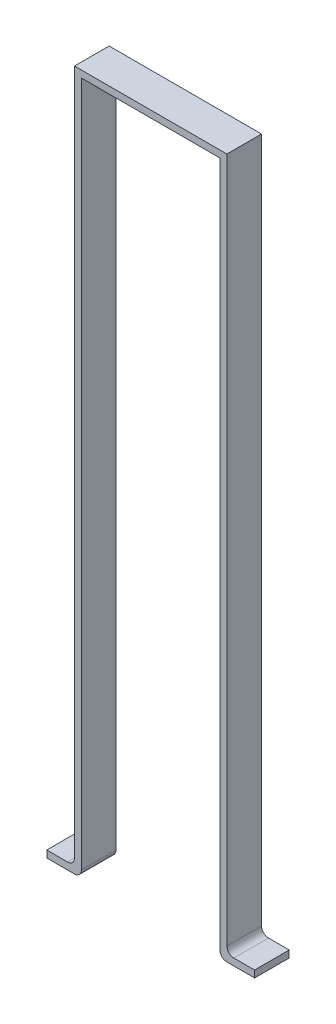
SolidWorks part; units mm, degrees
ref_plane "Front Plane" through (0, 0, 0) normal (0, 0, 1) x (1, 0, 0)
ref_plane "Top Plane" through (0, 0, 0) normal (0, 1, 0) x (1, 0, 0)
ref_plane "Right Plane" through (0, 0, 0) normal (1, 0, 0) x (0, 0, -1)
sketch "Sketch1" plane through (0, 0, 0) normal (0, 0, 1) x (1, 0, 0)
  line L0 (-25.4, 0) -> (25.4, 0) construction
  line L1 (-25.4, 2.54) -> (-25.4, 254)
  line L2 (-25.4, 254) -> (25.4, 254)
  line L3 (25.4, 254) -> (25.4, 2.54)
  line L4 (-27.94, 0) -> (-38.1, 0)
  line L5 (27.94, 0) -> (38.1, 0)
  line L6 (30.48, 2.54) -> (38.1, 2.54)
  line L7 (27.94, 256.54) -> (27.94, 5.08)
  line L8 (-27.94, 256.54) -> (27.94, 256.54)
  line L9 (-27.94, 5.08) -> (-27.94, 256.54)
  line L10 (-30.48, 2.54) -> (-38.1, 2.54)
  line L11 (-38.1, 2.54) -> (-38.1, 0)
  line L12 (38.1, 2.54) -> (38.1, 0)
  line L13 (-27.94, 2.54) -> (-27.94, 256.54) construction
  line L14 (-27.94, 2.54) -> (-38.1, 2.54) construction
  line L15 (-25.4, 0) -> (-38.1, 0) construction
  line L16 (-25.4, 0) -> (-25.4, 254) construction
  line L17 (25.4, 0) -> (38.1, 0) construction
  line L18 (25.4, 254) -> (25.4, 0) construction
  line L19 (27.94, 2.54) -> (38.1, 2.54) construction
  line L20 (27.94, 256.54) -> (27.94, 2.54) construction
  arc A0 (-27.94, 5.08) -> (-30.48, 2.54) centre (-30.48, 5.08) cw
  arc A1 (-27.94, 0) -> (-25.4, 2.54) centre (-27.94, 2.54) ccw
  arc A2 (27.94, 0) -> (25.4, 2.54) centre (27.94, 2.54) cw
  arc A3 (30.48, 2.54) -> (27.94, 5.08) centre (30.48, 5.08) cw
  point P3 (0, 0)
  dimension "D5" = 2.54
  dimension "D6" = 2.54
  dimension "D1" = 50.8
  dimension "D2" = 254
  dimension "D3" = 12.7
  dimension "D4" = 2.54
extrude "Boss-Extrude1" add sketch "Sketch1" along normal blind 12.7 contours L2 L3 A2 L5 L12 L6 A3 L7 L8 L9 A0 L10 L11 L4 A1 L1
